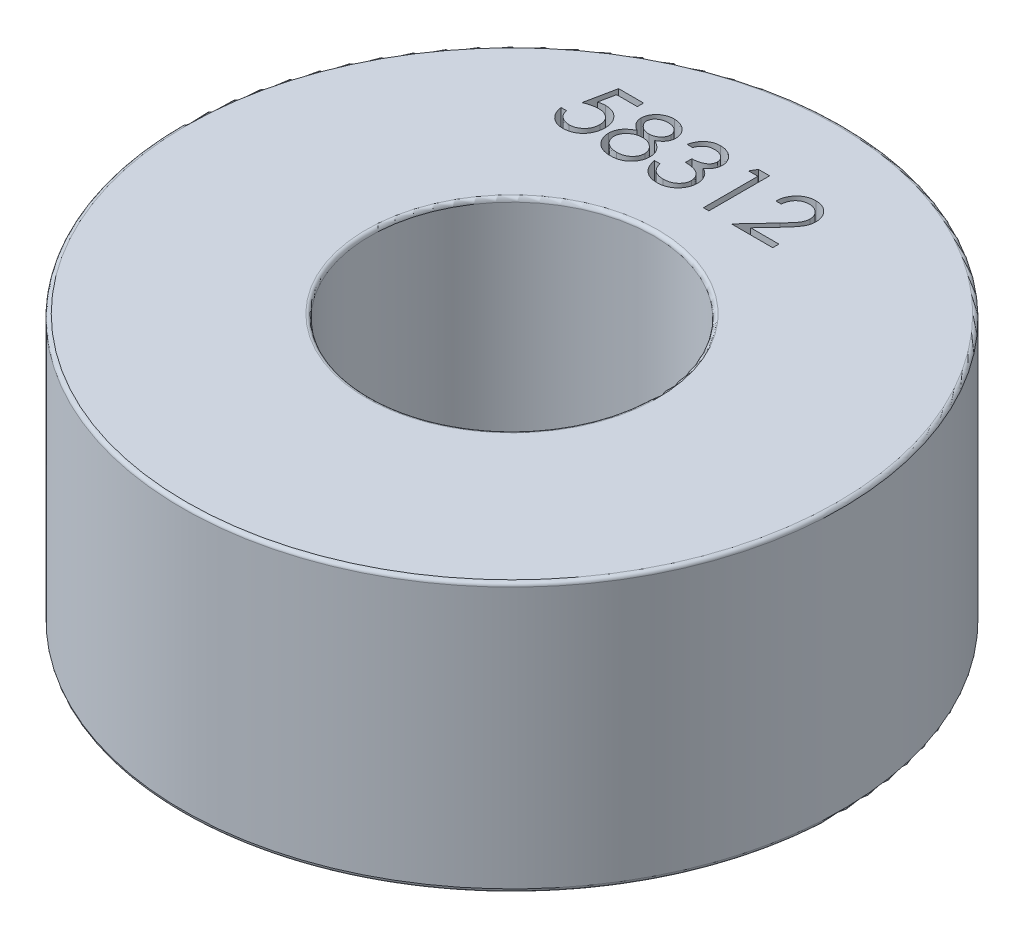
SolidWorks part; units mm, degrees
ref_plane "Front Plane" through (0, 0, 0) normal (0, 0, 1) x (1, 0, 0)
ref_plane "Top Plane" through (0, 0, 0) normal (0, 1, 0) x (1, 0, 0)
ref_plane "Right Plane" through (0, 0, 0) normal (1, 0, 0) x (0, 0, -1)
sketch "Toroidal Core TC229" plane through (0, 0, 0) normal (0, 0, 1) x (1, 0, 0)
  line L0 (0, -8.108) -> (0, 13.3131) construction
  line L2 (5.7191, 0) -> (12.7809, 0)
  line L3 (5.573, 0.1461) -> (5.573, 10.3979)
  line L4 (5.7191, 10.5439) -> (12.7809, 10.5439)
  line L5 (12.927, 0.1461) -> (12.927, 10.3979)
  arc A0 (5.7191, 0) -> (5.573, 0.1461) centre (5.7191, 0.1461) cw
  arc A1 (12.7809, 0) -> (12.927, 0.1461) centre (12.7809, 0.1461) ccw
  arc A2 (12.7809, 10.5439) -> (12.927, 10.3979) centre (12.7809, 10.3979) cw
  arc A3 (5.573, 10.3979) -> (5.7191, 10.5439) centre (5.7191, 10.3979) cw
  point P9 (5.573, 0)
  point P12 (12.927, 0)
  point P15 (12.927, 10.5439)
  point P18 (5.573, 10.5439)
  dimension "D4" = 0.1461
  dimension "D1" = 7.3539
  dimension "D2" = 10.5439
  dimension "D3" = 5.573
revolve "Revolve2" add sketch "Toroidal Core TC229" angle 360 about L0
sketch "Sketch1" plane through (0, 10.5439, 0) normal (0, 1, 0) x (1, 0, 0)
  text T0 "58312" font "Century Gothic" height in points 9
extrude "Cut-Extrude1" cut sketch "Sketch1" against normal blind 1
equation "\"FinishedODmax\"= 23.7mm"
equation "\"FinishedIDmin\"= 13.3mm"
equation "\"FinishedHTmax\"= 8.39mm"
equation "\"FinishedInnerRadiusmin\"= \"FinishedIDmin\" / 2"
equation "\"FinishedOuterRadiusmin\"= \"FinishedODmax\" / 2"
equation "\"Dia18AWG\"= .0424in'Single Build Magnet Wire per http://www.mwswire.com/pdf_files/mws_tech_book/page4_5_6_33_34.pdf"
equation "\"HT\"= \"FinishedHTmax\" + ( \"Dia18AWG\" * 2 )"
equation "\"InnerRadius\"= \"FinishedInnerRadiusmin\" - ( \"Dia18AWG\" * 1 )"
equation "\"OuterRadius\"= \"FinishedOuterRadiusmin\" + ( \"Dia18AWG\" * 1 )"
equation "\"D2@Toroidal Core TC229\"=\"HT\""
equation "\"D3@Toroidal Core TC229\"=\"InnerRadius\""
equation "\"D1@Toroidal Core TC229\"=\"OuterRadius\"-\"InnerRadius\""
equation "\"Wall\"= \"OuterRadius\" - \"InnerRadius\""
